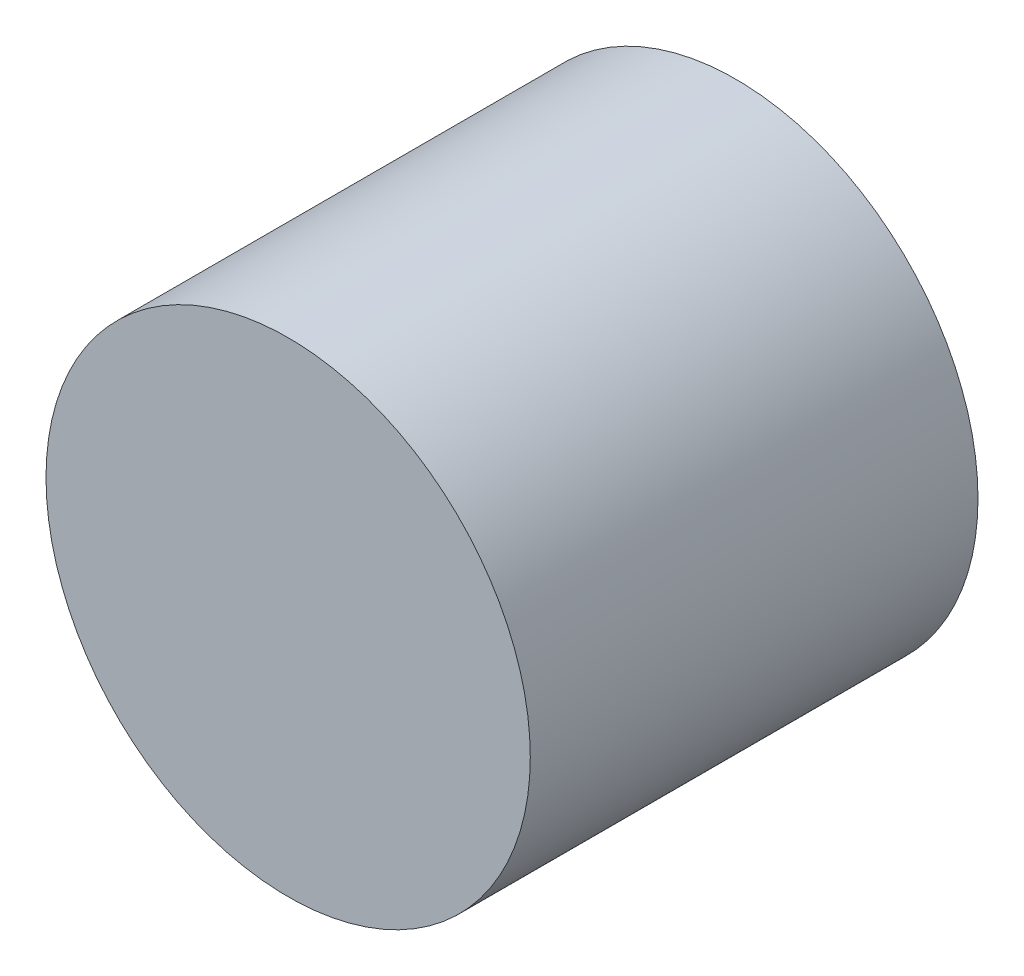
SolidWorks part; units mm, degrees
ref_plane "Front Plane" through (0, 0, 0) normal (0, 0, 1) x (1, 0, 0)
ref_plane "Top Plane" through (0, 0, 0) normal (0, 1, 0) x (1, 0, 0)
ref_plane "Right Plane" through (0, 0, 0) normal (1, 0, 0) x (0, 0, -1)
sketch "Sketch1" plane through (0, 0, 0) normal (0, 0, 1) x (1, 0, 0)
  circle A0 centre (0, 0) radius 48.1377
  circle A1 centre (0, 0) radius 45.1497
extrude "Boss-Extrude1" add sketch "Sketch1" along normal blind 83
sketch "Sketch2" plane through (0, 0, 83) normal (0, 0, 1) x (1, 0, 0)
  circle A0 centre (0, 0) radius 48.1377
extrude "Boss-Extrude2" add sketch "Sketch2" along normal blind 3
sketch "Sketch3" plane through (0, 0, 0) normal (0, 0, -1) x (-1, 0, 0)
  circle A0 centre (0, 0) radius 48.1377
extrude "Boss-Extrude3" add sketch "Sketch3" along normal blind 3
sketch "Sketch4" plane through (0, 0, -3) normal (0, 0, -1) x (-1, 0, 0)
  circle A0 centre (0, 0) radius 20.8531
extrude "Cut-Extrude1" cut sketch "Sketch4" against normal blind 17
